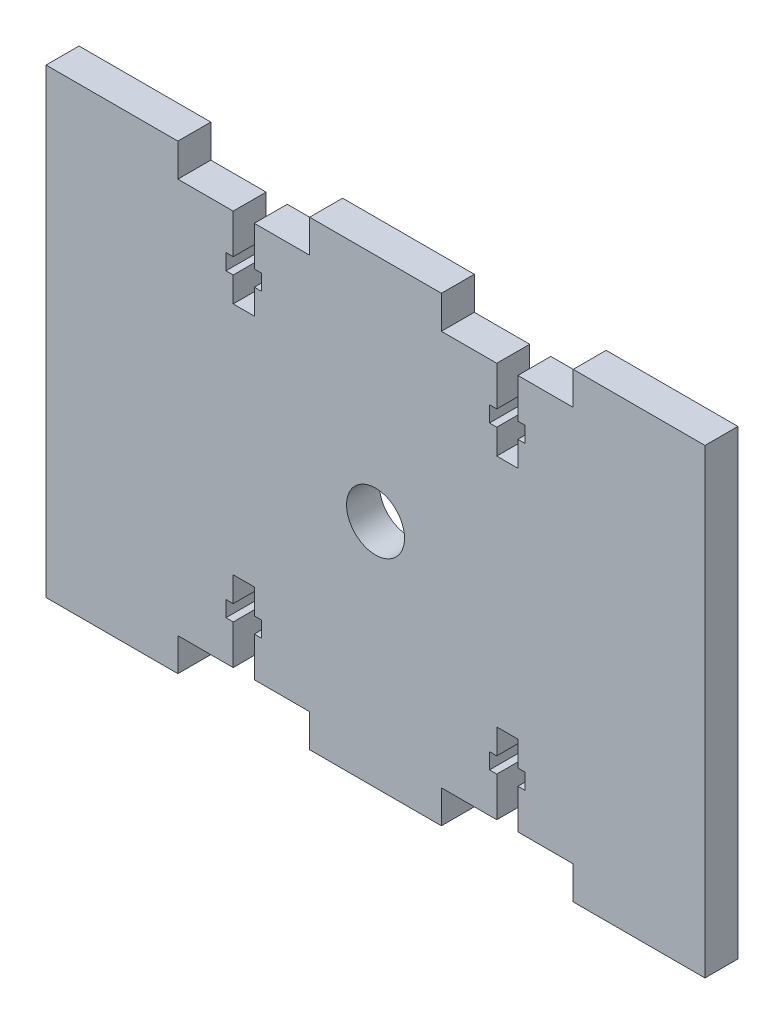
SolidWorks part; units mm, degrees
ref_plane "Front" through (0, 0, 0) normal (0, 0, 1) x (1, 0, 0)
ref_plane "Top" through (0, 0, 0) normal (0, 1, 0) x (1, 0, 0)
ref_plane "Right" through (0, 0, 0) normal (1, 0, 0) x (0, 0, -1)
sketch "Sketch2" plane through (0, 0, 0) normal (0, 0, 1) x (1, 0, 0)
  line L1 (-63.5, 38.1) -> (63.5, 38.1)
  line L2 (-63.5, 38.1) -> (-63.5, -38.1)
  line L3 (-63.5, -38.1) -> (63.5, -38.1)
  line L4 (63.5, 38.1) -> (63.5, -38.1)
  line L5 (-63.5, 38.1) -> (63.5, -38.1) construction
  line L6 (-63.5, -38.1) -> (63.5, 38.1) construction
  point P0 (0, 0)
  dimension "D1" = 76.2
  dimension "D2" = 127
extrude "Boss-Extrude1" add sketch "Sketch2" along normal blind 6.35
sketch "Sketch3" plane through (0, 0, 6.35) normal (0, 0, 1) x (1, 0, 0)
  line L0 (0, 38.1) -> (0, -38.4249) construction
  line L1 (63.5, 38.1) -> (-63.5, 38.1) construction
  line L2 (0, -50) -> (0, 50) construction
  line L3 (-63.5, 0) -> (63.5, 0) construction
  line L4 (-63.5, 38.1) -> (-63.5, -38.1) construction
  line L5 (63.5, -38.1) -> (63.5, 38.1) construction
  line L6 (38.1, 38.1) -> (38.1, 44.45)
  line L7 (-12.7, 38.1) -> (12.7, 38.1)
  line L8 (-12.7, 38.1) -> (-12.7, 44.45)
  line L9 (-12.7, 44.45) -> (12.7, 44.45)
  line L10 (12.7, 38.1) -> (12.7, 44.45)
  line L11 (-63.5, 38.1) -> (-38.1, 38.1)
  line L12 (-63.5, 38.1) -> (-63.5, 44.45)
  line L13 (-63.5, 44.45) -> (-38.1, 44.45)
  line L14 (-38.1, 38.1) -> (-38.1, 44.45)
  line L15 (63.5, 44.45) -> (38.1, 44.45)
  line L16 (63.5, 38.1) -> (63.5, 44.45)
  line L17 (63.5, 38.1) -> (38.1, 38.1)
  line L18 (-12.7, 38.1) -> (-12.7, 44.45)
  line L19 (12.7, 38.1) -> (12.7, 44.45)
  line L20 (12.7, -38.1) -> (12.7, -44.45)
  line L21 (-12.7, -38.1) -> (-12.7, -44.45)
  line L22 (63.5, -38.1) -> (38.1, -38.1)
  line L23 (63.5, -38.1) -> (63.5, -44.45)
  line L24 (63.5, -44.45) -> (38.1, -44.45)
  line L25 (-38.1, -38.1) -> (-38.1, -44.45)
  line L26 (-63.5, -44.45) -> (-38.1, -44.45)
  line L27 (-63.5, -38.1) -> (-63.5, -44.45)
  line L28 (-63.5, -38.1) -> (-38.1, -38.1)
  line L29 (12.7, -38.1) -> (12.7, -44.45)
  line L30 (-12.7, -44.45) -> (12.7, -44.45)
  line L31 (-12.7, -38.1) -> (-12.7, -44.45)
  line L32 (-12.7, -38.1) -> (12.7, -38.1)
  line L33 (38.1, -38.1) -> (38.1, -44.45)
  point P17 (0, 38.1)
  line M2 (63.5, 38.1) -> (-63.5, 38.1)
  line M4 (-63.5, -38.1) -> (63.5, -38.1)
  dimension "D1" = 25.4
  dimension "D2" = 6.35
  dimension "D3" = 25.4
extrude "Boss-Extrude2" add sketch "Sketch3" against normal blind 6.35 contours L10 L9 L8 M2 | L16 L15 L6 M2 | L33 L24 L23 M4 | L21 L30 L20 M4 | L27 L26 L25 M4 | L11 L14 L13 L12
sketch "Sketch4" plane through (0, 0, 6.35) normal (0, 0, 1) x (1, 0, 0)
  line L0 (-12.7, 38.1) -> (-38.1, 38.1) construction
  line L1 (0, 44.45) -> (0, -44.0615) construction
  line L2 (-12.7, 44.45) -> (12.7, 44.45) construction
  line L3 (0, -50) -> (0, 50) construction
  line L4 (-63.5, 0) -> (63.3101, 0) construction
  line L5 (-63.5, 44.45) -> (-63.5, -44.45) construction
  line L6 (50, 0) -> (-50, 0) construction
  point P17 (-25.4, 38.1)
  line B0 (-27.432, 38.1) -> (-23.368, 38.1)
  line B1 (-27.432, 38.1) -> (-27.432, 30.48)
  line B2 (-27.432, 22.606) -> (-23.368, 22.606)
  line B3 (-23.368, 38.1) -> (-23.368, 30.48)
  line B4 (-25.4, 38.1) -> (-25.4, 22.606) construction
  line B5 (-23.368, 30.48) -> (-21.971, 30.48)
  line B6 (-28.829, 30.48) -> (-27.432, 30.48)
  line B7 (-28.829, 30.48) -> (-28.829, 27.432)
  line B8 (-28.829, 27.432) -> (-27.432, 27.432)
  line B9 (-21.971, 30.48) -> (-21.971, 27.432)
  line B10 (-28.829, 30.48) -> (-21.971, 27.432) construction
  line B11 (-28.829, 27.432) -> (-21.971, 30.48) construction
  line B12 (-23.368, 27.432) -> (-23.368, 22.606)
  line B13 (-27.432, 27.432) -> (-27.432, 22.606)
  line B14 (-23.368, 27.432) -> (-21.971, 27.432)
  line B15 (27.432, 38.1) -> (23.368, 38.1)
  line B16 (27.432, 38.1) -> (27.432, 30.48)
  line B17 (27.432, 22.606) -> (23.368, 22.606)
  line B18 (23.368, 38.1) -> (23.368, 30.48)
  line B19 (23.368, 30.48) -> (21.971, 30.48)
  line B20 (28.829, 30.48) -> (27.432, 30.48)
  line B21 (28.829, 30.48) -> (28.829, 27.432)
  line B22 (28.829, 27.432) -> (27.432, 27.432)
  line B23 (21.971, 30.48) -> (21.971, 27.432)
  line B24 (23.368, 27.432) -> (23.368, 22.606)
  line B25 (27.432, 27.432) -> (27.432, 22.606)
  line B26 (23.368, 27.432) -> (21.971, 27.432)
  line B27 (27.432, -38.1) -> (23.368, -38.1)
  line B28 (27.432, -38.1) -> (27.432, -30.48)
  line B29 (27.432, -22.606) -> (23.368, -22.606)
  line B30 (23.368, -38.1) -> (23.368, -30.48)
  line B31 (23.368, -30.48) -> (21.971, -30.48)
  line B32 (28.829, -30.48) -> (27.432, -30.48)
  line B33 (28.829, -30.48) -> (28.829, -27.432)
  line B34 (28.829, -27.432) -> (27.432, -27.432)
  line B35 (21.971, -30.48) -> (21.971, -27.432)
  line B36 (23.368, -27.432) -> (23.368, -22.606)
  line B37 (27.432, -27.432) -> (27.432, -22.606)
  line B38 (23.368, -27.432) -> (21.971, -27.432)
  line B39 (-27.432, -38.1) -> (-23.368, -38.1)
  line B40 (-27.432, -38.1) -> (-27.432, -30.48)
  line B41 (-27.432, -22.606) -> (-23.368, -22.606)
  line B42 (-23.368, -38.1) -> (-23.368, -30.48)
  line B43 (-23.368, -30.48) -> (-21.971, -30.48)
  line B44 (-28.829, -30.48) -> (-27.432, -30.48)
  line B45 (-28.829, -30.48) -> (-28.829, -27.432)
  line B46 (-28.829, -27.432) -> (-27.432, -27.432)
  line B47 (-21.971, -30.48) -> (-21.971, -27.432)
  line B48 (-23.368, -27.432) -> (-23.368, -22.606)
  line B49 (-27.432, -27.432) -> (-27.432, -22.606)
  line B50 (-23.368, -27.432) -> (-21.971, -27.432)
sketch_block_instance "Block2-1"
sketch_block "Block2" parameters "D1"=15.494, "D2"=4.064, "D3"=3.048, "D4"=6.858
sketch_block_instance "Block2-3"
sketch_block_instance "Block2-4"
sketch_block_instance "Block2-5"
extrude "Cut-Extrude1" cut sketch "Sketch4" against normal through all
sketch "Sketch5" plane through (0, 0, 6.35) normal (0, 0, 1) x (1, 0, 0)
  circle A0 centre (0, 0) radius 5.588
  dimension "D1" = 11.176
extrude "Cut-Extrude2" cut sketch "Sketch5" against normal through all
